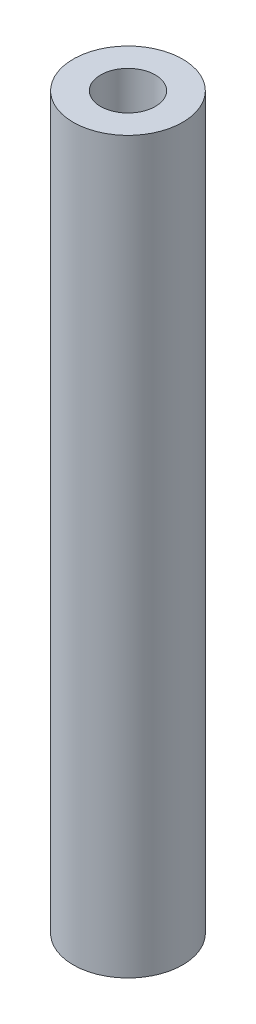
SolidWorks part; units mm, degrees
ref_plane "Front Plane" through (0, 0, 0) normal (0, 0, 1) x (1, 0, 0)
ref_plane "Top Plane" through (0, 0, 0) normal (0, 1, 0) x (1, 0, 0)
ref_plane "Right Plane" through (0, 0, 0) normal (1, 0, 0) x (0, 0, -1)
sketch "Sketch1" plane through (0, 0, 0) normal (0, 1, 0) x (1, 0, 0)
  circle A0 centre (0, 0) radius 1.5
  circle A1 centre (0, 0) radius 3
  dimension "D1" = 3
  dimension "D2" = 6
extrude "Boss-Extrude1" add sketch "Sketch1" along normal blind 40
